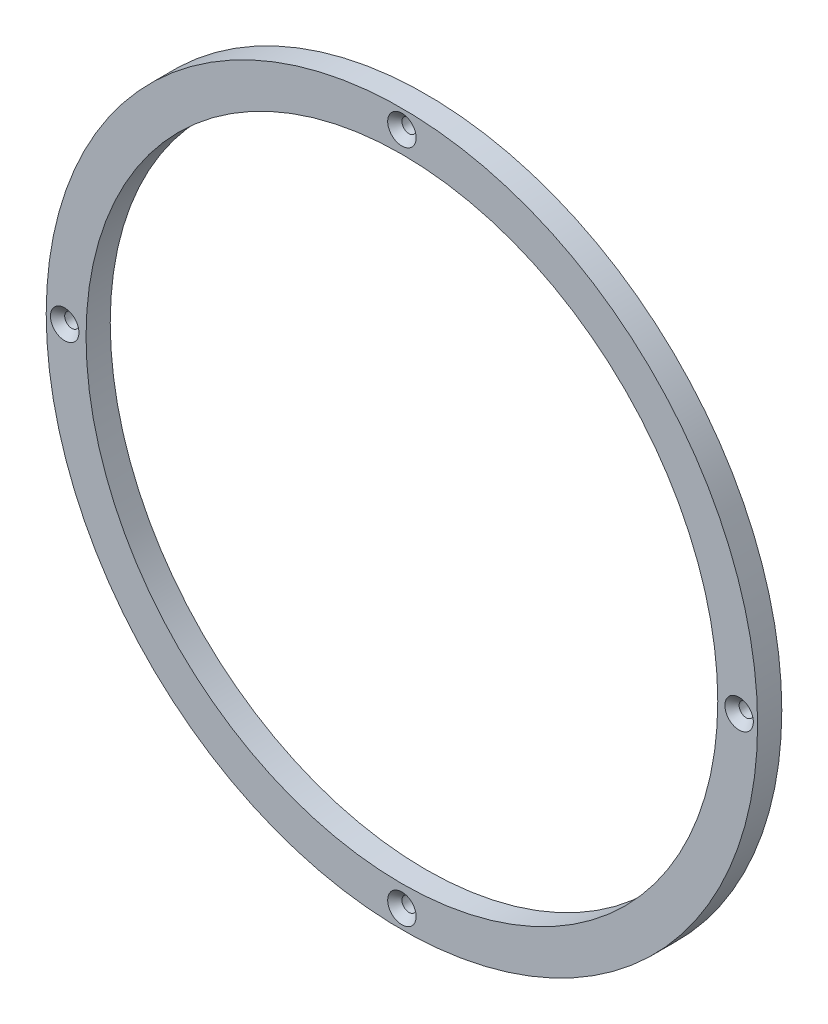
SolidWorks part; units mm, degrees
material "Lega 1060"
ref_plane "Piano frontale" through (0, 0, 0) normal (0, 0, 1) x (1, 0, 0)
ref_plane "Piano superiore" through (0, 0, 0) normal (0, 1, 0) x (1, 0, 0)
ref_plane "Piano destro" through (0, 0, 0) normal (1, 0, 0) x (0, 0, -1)
sketch "Schizzo1" plane through (0, 0, 0) normal (0, 0, 1) x (1, 0, 0)
  circle A0 centre (0, 0) radius 111
  circle A1 centre (0, 0) radius 125
  dimension "D1" = 14
  dimension "D2" = 250
extrude "Estrusione-Estrusione1" add sketch "Schizzo1" along normal blind 8.5 contours A1 A0 | A0
hole_wizard "Foro svasato per Vite M4 a testa svasata cilindrica2" positions "Schizzo4" profile "Schizzo5" countersink size "M4" standard "DIN" end condition through all
sketch "Schizzo4" plane through (0, 0, 8.5) normal (0, 0, 1) x (1, 0, 0)
  line L0 (0, -4.675) -> (0, 4.675) construction
  circle A0 centre (0, 0) radius 125 construction
  point P0 (0, -118.5)
  dimension "D1" = 6.5
sketch "Schizzo5" plane through (0, -118.5, 8.5) normal (1, 0, 0) x (0, -1, 0)
  line L0 (0, 0) -> (0, 8.5)
  line L1 (0, 8.5) -> (2.5, 8.5)
  line L2 (2.5, 8.5) -> (2.5, 2.5)
  line L3 (2.5, 2.5) -> (5, 0)
  line L5 (5, 0) -> (0, 0)
  line L6 (-2.5, 2.5) -> (-5, 0) construction
  line L11 (0, -6.35) -> (0, 107.95) construction
  dimension "Thru Hole Dia." = 5
  dimension "Thru Hole Depth" = 8.5
  dimension "Near C'Sink Dia." = 10
  dimension "Near C'Sink Angle" = 90
pattern_circular "RipetizioneCircolare1" count 4 over 360 about axis through (0, 0, 0) along (0, 0, 1) of "Foro svasato per Vite M4 a testa svasata cilindrica2"
